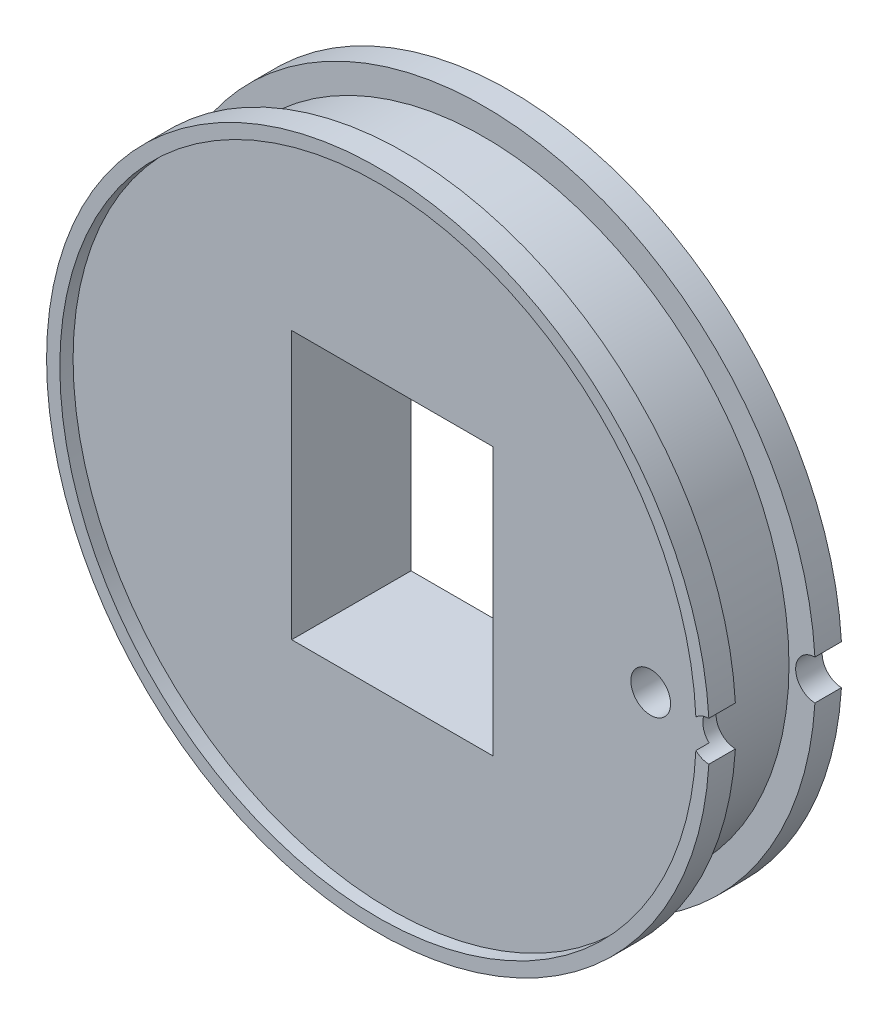
SolidWorks part; units mm, degrees
ref_plane "Ebene vorne" through (0, 0, 0) normal (0, 0, 1) x (1, 0, 0)
ref_plane "Ebene oben" through (0, 0, 0) normal (0, 1, 0) x (1, 0, 0)
ref_plane "Ebene rechts" through (0, 0, 0) normal (1, 0, 0) x (0, 0, -1)
sketch "Skizze1" plane through (0, 0, 0) normal (0, 0, 1) x (1, 0, 0)
  circle A0 centre (0, 0) radius 25
  dimension "D1" = 50
extrude "Aufsatz-Linear austragen1" add sketch "Skizze1" along normal blind 9
sketch "Skizze3" plane through (0, 0, 9) normal (0, 0, 1) x (1, 0, 0)
  circle A0 centre (0, 0) radius 25
  circle A1 centre (0, 0) radius 24
  dimension "D1" = 48
extrude "Aufsatz-Linear austragen2" add sketch "Skizze3" along normal blind 1
sketch "Skizze4" plane through (0, 0, 9) normal (0, 0, 1) x (1, 0, 0)
  line L1 (-7.51, 10.1) -> (7.69, 10.1)
  line L2 (-7.51, 10.1) -> (-7.51, -10.1)
  line L3 (-7.51, -10.1) -> (7.69, -10.1)
  line L4 (7.69, 10.1) -> (7.69, -10.1)
  point P7 (-0.7261, -0.1452)
  point P8 (-1.1618, 0.0726)
  dimension "D1" = 15.2
  dimension "D2" = 20.2
  dimension "D3" = 10.1
  dimension "D4" = 7.51
extrude "Schnitt-Linear austragen1" cut sketch "Skizze4" against normal up to next
ref_plane "Ebene1" through (0, 0, 2) normal (0, 0, -1) x (-1, 0, 0)
sketch "Skizze6" plane through (0, 0, 2) normal (0, 0, -1) x (-1, 0, 0)
  circle A0 centre (0, 0) radius 25
  circle A1 centre (0, 0) radius 23
  dimension "D1" = 46
extrude "Schnitt-Linear austragen2" cut sketch "Skizze6" against normal blind 6
sketch "Skizze7" plane through (0, 0, 0) normal (0, 0, -1) x (-1, 0, 0)
  circle A0 centre (-19.5695, 0) radius 1.5
  dimension "D1" = 3
extrude "Schnitt-Linear austragen3" cut sketch "Skizze7" against normal through all
sketch "Skizze8" plane through (0, 0, 0) normal (0, 0, -1) x (-1, 0, 0)
  circle A0 centre (-25, 0) radius 1.5
  circle A1 centre (0, 0) radius 25 construction
  dimension "D1" = 3
extrude "Schnitt-Linear austragen4" cut sketch "Skizze8" against normal through all
